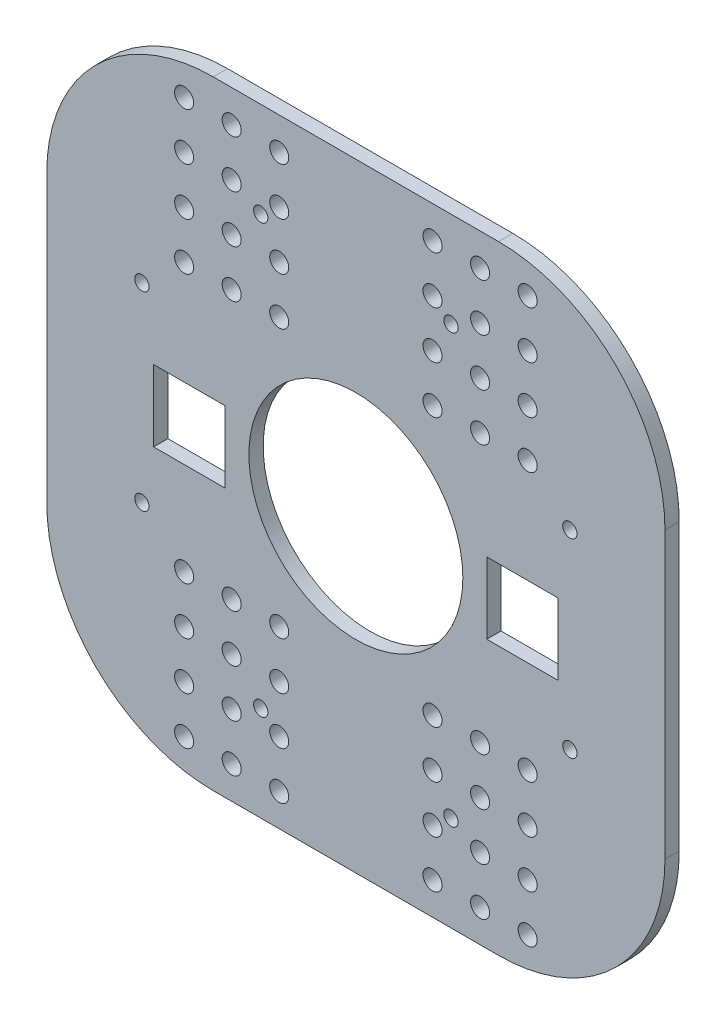
SolidWorks part; units mm, degrees
ref_plane "前视基准面" through (0, 0, 0) normal (0, 0, 1) x (1, 0, 0)
ref_plane "上视基准面" through (0, 0, 0) normal (0, 1, 0) x (1, 0, 0)
ref_plane "右视基准面" through (0, 0, 0) normal (1, 0, 0) x (0, 0, -1)
sketch "草图1" plane through (0, 0, 0) normal (0, 0, 1) x (1, 0, 0)
  line L1 (-65, 65) -> (65, 65)
  line L2 (-65, 65) -> (-65, -65)
  line L3 (-65, -65) -> (65, -65)
  line L4 (65, 65) -> (65, -65)
  line L5 (-65, 65) -> (65, -65) construction
  line L6 (-65, -65) -> (65, 65) construction
  circle A0 centre (0, 0) radius 22.5
  point P0 (0, 0)
extrude "凸台-拉伸1" add sketch "草图1" against normal blind 3
fillet "圆角1" radius 35 4 edges at (65, 65, -1.5) (-65, 65, -1.5) (65, -65, -1.5) (-65, -65, -1.5)
sketch "草图5" plane through (0, 0, -3) normal (0, 0, -1) x (-1, 0, 0)
  line L4 (42.532, -8.6552) -> (42.532, 6.3448)
  line L5 (42.532, 6.3448) -> (27.532, 6.3448)
  line L6 (27.532, 6.3448) -> (27.532, -8.6552)
  line L7 (27.532, -8.6552) -> (42.532, -8.6552)
  line L8 (42.532, -8.6552) -> (42.532, 6.3448)
  line L9 (42.532, 6.3448) -> (27.532, 6.3448)
  line L10 (27.532, 6.3448) -> (27.532, -8.6552)
  line L11 (27.532, -8.6552) -> (42.532, -8.6552)
  line L12 (-27.532, 6.3448) -> (-42.532, 6.3448)
  line L13 (-42.532, 6.3448) -> (-42.532, -8.6552)
  line L14 (-42.532, -8.6552) -> (-27.532, -8.6552)
  line L15 (-27.532, -8.6552) -> (-27.532, 6.3448)
  line L16 (-27.532, 6.3448) -> (-42.532, 6.3448)
  line L17 (-42.532, 6.3448) -> (-42.532, -8.6552)
  line L18 (-42.532, -8.6552) -> (-27.532, -8.6552)
  line L19 (-27.532, -8.6552) -> (-27.532, 6.3448)
  circle A1 centre (36.1191, 58.1968) radius 2
  circle A2 centre (36.1191, 58.1968) radius 2
  circle A3 centre (36.1191, 48.1968) radius 2
  circle A4 centre (36.1191, 48.1968) radius 2
  circle A5 centre (36.1191, 38.1968) radius 2
  circle A6 centre (36.1191, 38.1968) radius 2
  circle A7 centre (-36.1191, -58.1968) radius 2
  circle A8 centre (-36.1191, -58.1968) radius 2
  circle A9 centre (16.1191, 48.1968) radius 2
  circle A10 centre (16.1191, 48.1968) radius 2
  circle A11 centre (16.1191, 38.1968) radius 2
  circle A12 centre (16.1191, 38.1968) radius 2
  circle A13 centre (16.1191, 28.1968) radius 2
  circle A14 centre (16.1191, 28.1968) radius 2
  circle A15 centre (26.1191, 58.1968) radius 2
  circle A16 centre (26.1191, 58.1968) radius 2
  circle A17 centre (16.1191, -48.1968) radius 2
  circle A18 centre (16.1191, -48.1968) radius 2
  circle A19 centre (26.1191, -28.1968) radius 2
  circle A20 centre (26.1191, -28.1968) radius 2
  circle A21 centre (36.1191, 28.1968) radius 2
  circle A22 centre (36.1191, 28.1968) radius 2
  circle A23 centre (26.1191, 48.1968) radius 2
  circle A24 centre (26.1191, 48.1968) radius 2
  circle A25 centre (26.1191, 38.1968) radius 2
  circle A26 centre (26.1191, 38.1968) radius 2
  circle A27 centre (26.1191, 28.1968) radius 2
  circle A28 centre (26.1191, 28.1968) radius 2
  circle A29 centre (16.1191, 58.1968) radius 2
  circle A30 centre (16.1191, 58.1968) radius 2
  circle A31 centre (16.1191, -58.1968) radius 2
  circle A32 centre (16.1191, -58.1968) radius 2
  circle A33 centre (26.1191, -58.1968) radius 2
  circle A34 centre (26.1191, -58.1968) radius 2
  circle A35 centre (16.1191, -28.1968) radius 2
  circle A36 centre (16.1191, -28.1968) radius 2
  circle A37 centre (16.1191, -38.1968) radius 2
  circle A38 centre (16.1191, -38.1968) radius 2
  circle A39 centre (36.1191, -38.1968) radius 2
  circle A40 centre (36.1191, -38.1968) radius 2
  circle A41 centre (36.1191, -48.1968) radius 2
  circle A42 centre (36.1191, -48.1968) radius 2
  circle A43 centre (36.1191, -58.1968) radius 2
  circle A44 centre (36.1191, -58.1968) radius 2
  circle A45 centre (-36.1191, -48.1968) radius 2
  circle A46 centre (-36.1191, -48.1968) radius 2
  circle A47 centre (-36.1191, -38.1968) radius 2
  circle A48 centre (-36.1191, -38.1968) radius 2
  circle A49 centre (-16.1191, -38.1968) radius 2
  circle A50 centre (-16.1191, -38.1968) radius 2
  circle A51 centre (-16.1191, -28.1968) radius 2
  circle A52 centre (-16.1191, -28.1968) radius 2
  circle A53 centre (-26.1191, -58.1968) radius 2
  circle A54 centre (-26.1191, -58.1968) radius 2
  circle A55 centre (26.1191, -38.1968) radius 2
  circle A56 centre (26.1191, -38.1968) radius 2
  circle A57 centre (26.1191, -48.1968) radius 2
  circle A58 centre (26.1191, -48.1968) radius 2
  circle A59 centre (36.1191, -28.1968) radius 2
  circle A60 centre (36.1191, -28.1968) radius 2
  circle A61 centre (-36.1191, -28.1968) radius 2
  circle A62 centre (-36.1191, -28.1968) radius 2
  circle A63 centre (-26.1191, -48.1968) radius 2
  circle A64 centre (-26.1191, -48.1968) radius 2
  circle A65 centre (-26.1191, -38.1968) radius 2
  circle A66 centre (-26.1191, -38.1968) radius 2
  circle A67 centre (-26.1191, -28.1968) radius 2
  circle A68 centre (-26.1191, -28.1968) radius 2
  circle A69 centre (-16.1191, -48.1968) radius 2
  circle A70 centre (-16.1191, -48.1968) radius 2
  circle A71 centre (-16.1191, 28.1968) radius 2
  circle A72 centre (-16.1191, 28.1968) radius 2
  circle A73 centre (-16.1191, 38.1968) radius 2
  circle A74 centre (-16.1191, 38.1968) radius 2
  circle A75 centre (-16.1191, 48.1968) radius 2
  circle A76 centre (-16.1191, 48.1968) radius 2
  circle A77 centre (-26.1191, 28.1968) radius 2
  circle A78 centre (-26.1191, 28.1968) radius 2
  circle A79 centre (-26.1191, 38.1968) radius 2
  circle A80 centre (-26.1191, 38.1968) radius 2
  circle A81 centre (-36.1191, 38.1968) radius 2
  circle A82 centre (-36.1191, 38.1968) radius 2
  circle A83 centre (-36.1191, 48.1968) radius 2
  circle A84 centre (-36.1191, 48.1968) radius 2
  circle A85 centre (-36.1191, 58.1968) radius 2
  circle A86 centre (-36.1191, 58.1968) radius 2
  circle A87 centre (-16.1191, -58.1968) radius 2
  circle A88 centre (-16.1191, -58.1968) radius 2
  circle A89 centre (-16.1191, 58.1968) radius 2
  circle A90 centre (-16.1191, 58.1968) radius 2
  circle A91 centre (-26.1191, 58.1968) radius 2
  circle A92 centre (-26.1191, 58.1968) radius 2
  circle A93 centre (-26.1191, 48.1968) radius 2
  circle A94 centre (-26.1191, 48.1968) radius 2
  circle A95 centre (-36.1191, 28.1968) radius 2
  circle A96 centre (-36.1191, 28.1968) radius 2
  dimension "D1" = 0
  dimension "D2" = 0
  dimension "D3" = 0
  dimension "D4" = 0
  dimension "D5" = 0
  dimension "D6" = 0
  dimension "D7" = 0
  dimension "D8" = 0
  dimension "D9" = 0
  dimension "D10" = 0
  dimension "D11" = 0
  dimension "D12" = 0
  dimension "D13" = 0
  dimension "D14" = 0
  dimension "D15" = 0
  dimension "D16" = 0
  dimension "D17" = 0
  dimension "D18" = 0
  dimension "D19" = 0
  dimension "D20" = 0
  dimension "D21" = 0
  dimension "D22" = 0
  dimension "D23" = 0
  dimension "D24" = 0
  dimension "D25" = 0
  dimension "D26" = 0
  dimension "D27" = 0
  dimension "D28" = 0
  dimension "D29" = 0
  dimension "D30" = 0
  dimension "D31" = 0
  dimension "D32" = 0
  dimension "D33" = 0
  dimension "D34" = 0
  dimension "D35" = 0
  dimension "D36" = 0
  dimension "D37" = 0
  dimension "D38" = 0
  dimension "D39" = 0
  dimension "D40" = 0
  dimension "D41" = 0
  dimension "D42" = 0
  dimension "D43" = 0
  dimension "D44" = 0
  dimension "D45" = 0
  dimension "D46" = 0
  dimension "D47" = 0
  dimension "D48" = 0
  dimension "D49" = 0
  dimension "D50" = 0
extrude "切除-拉伸2" cut sketch "草图5" against normal blind 13
sketch "草图6" plane through (0, 0, 0) normal (0, 0, 1) x (1, 0, 0)
  circle A0 centre (-45, 20) radius 1.5
  circle A1 centre (45, 20) radius 1.5
  circle A2 centre (45, -20) radius 1.5
  circle A3 centre (-45, -20) radius 1.5
  dimension "D3" = 3
  dimension "D1" = 45
  dimension "D2" = 20
  dimension "D4" = 2
  dimension "D5" = 2
extrude "切除-拉伸3" cut sketch "草图6" against normal through all
sketch "草图7" plane through (0, 0, 0) normal (0, 0, 1) x (1, 0, 0)
  circle A0 centre (-20, 45) radius 1.5
  circle A1 centre (20, 45) radius 1.5
  circle A2 centre (20, -45) radius 1.5
  circle A3 centre (-20, -45) radius 1.5
  dimension "D1" = 3
  dimension "D2" = 20
  dimension "D3" = 45
  dimension "D4" = 2
  dimension "D5" = 2
extrude "切除-拉伸4" cut sketch "草图7" against normal through all
